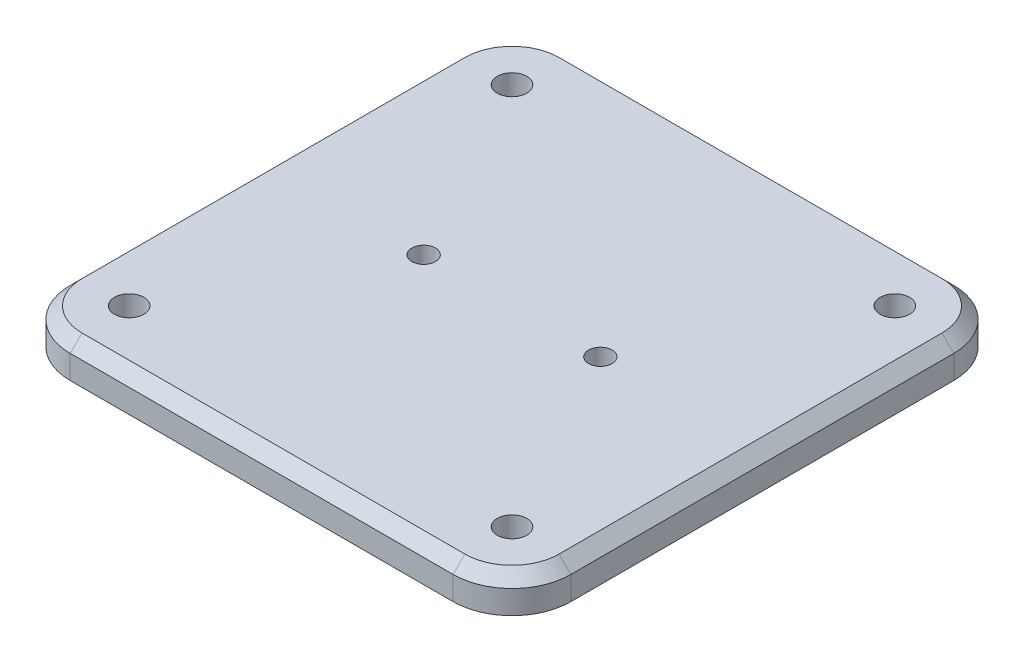
SolidWorks part; units mm, degrees
ref_plane "Front Plane" through (0, 0, 0) normal (0, 0, 1) x (1, 0, 0)
ref_plane "Top Plane" through (0, 0, 0) normal (0, 1, 0) x (1, 0, 0)
ref_plane "Right Plane" through (0, 0, 0) normal (1, 0, 0) x (0, 0, -1)
sketch "Sketch1" plane through (0, 0, 0) normal (0, 1, 0) x (1, 0, 0)
  line L1 (-32.5, -42.5) -> (32.5, -42.5)
  line L2 (-42.5, -32.5) -> (-42.5, 32.5)
  line L3 (-32.5, 42.5) -> (32.5, 42.5)
  line L4 (42.5, -32.5) -> (42.5, 32.5)
  arc A0 (-32.5, -42.5) -> (-42.5, -32.5) centre (-32.5, -32.5) cw
  arc A1 (32.5, -42.5) -> (42.5, -32.5) centre (32.5, -32.5) ccw
  arc A2 (32.5, 42.5) -> (42.5, 32.5) centre (32.5, 32.5) cw
  arc A3 (-42.5, 32.5) -> (-32.5, 42.5) centre (-32.5, 32.5) cw
  circle A4 centre (-32.5, 32.5) radius 2.5
  circle A5 centre (32.5, 32.5) radius 2.5
  circle A6 centre (32.5, -32.5) radius 2.5
  circle A7 centre (-32.5, -32.5) radius 2.5
  point P1 (0, 0)
  dimension "D1" = 10
  dimension "D2" = 5
  dimension "D3" = 42.5
  dimension "D4" = 42.5
  dimension "D5" = 42.5
extrude "Boss-Extrude1" add sketch "Sketch1" along normal blind 6
chamfer "Chamfer1" distance 2 angle 45 5 edges at (39.5711, 6, -39.5711) (42.5, 6, 0) (39.5711, 6, 39.5711) (0, 6, 42.5) (-39.5711, 6, 39.5711)
hole_wizard "M4x0.7 Tapped Hole2" positions "Sketch4" profile "Sketch5" tap size "M4x0.7" standard "ANSI Metric"
sketch "Sketch4" plane through (0, 6, 0) normal (0, 1, 0) x (1, 0, 0)
  line L0 (-42.5, -32.5) -> (-42.5, 32.5) construction
  point P0 (-15, 0)
  point P2 (15, 0)
  dimension "D1" = 27.5
  dimension "D2" = 30
sketch "Sketch5" plane through (-15, 6, 0) normal (1, 0, 0) x (0, 0, 1)
  line L0 (0, 0) -> (0, 10.1)
  line L1 (0, 10.1) -> (2, 8.8983)
  line L2 (2, 8.8983) -> (2, 0)
  line L5 (2, 0) -> (0, 0)
  line L10 (0, 10.1) -> (-2, 8.8983) construction
  line L11 (0, -6.35) -> (0, 107.95) construction
  dimension "Tap Drill Dia." = 4
  dimension "Tap Drill Depth" = 10.1
  dimension "Drill Angle" = 118
cosmetic thread "Hole Thread3" parameters "D1"=8, "D2"=4
cosmetic thread "Hole Thread4" parameters "D1"=8, "D2"=4
